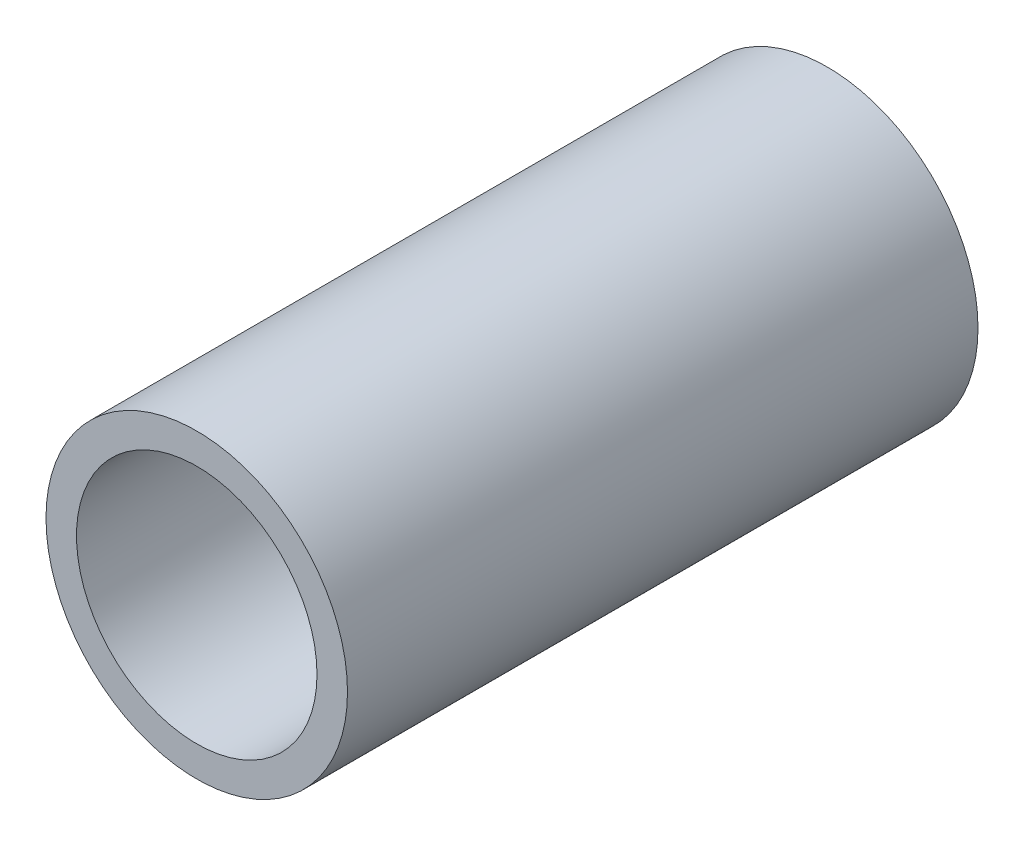
SolidWorks part; units mm, degrees
ref_plane "Front Plane" through (0, 0, 0) normal (0, 0, 1) x (1, 0, 0)
ref_plane "Top Plane" through (0, 0, 0) normal (0, 1, 0) x (1, 0, 0)
ref_plane "Right Plane" through (0, 0, 0) normal (1, 0, 0) x (0, 0, -1)
sketch "Sketch1" plane through (0, 0, 0) normal (0, 0, 1) x (1, 0, 0)
  circle A0 centre (0, 0) radius 16.7005
  dimension "Pipe OD" = 33.401
extrude "Extrude-Thin1" add sketch "Sketch1" along normal mid plane 69.85 thin thin type one direction reverse wall 3.3782
